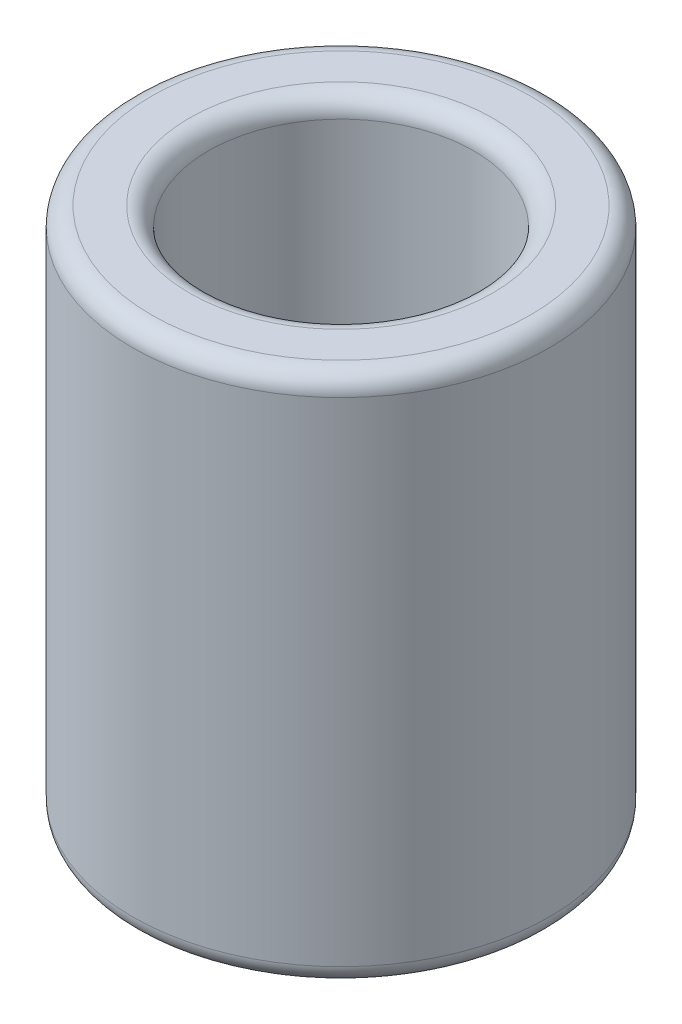
SolidWorks part; units mm, degrees
ref_plane "Front Plane" through (0, 0, 0) normal (0, 0, 1) x (1, 0, 0)
ref_plane "Top Plane" through (0, 0, 0) normal (0, 1, 0) x (1, 0, 0)
ref_plane "Right Plane" through (0, 0, 0) normal (1, 0, 0) x (0, 0, -1)
sketch "Sketch1" plane through (0, 0, 0) normal (0, 1, 0) x (1, 0, 0)
  circle A0 centre (0, 0) radius 1.75
  circle A1 centre (0, 0) radius 2.75
  dimension "D1" = 3.5
  dimension "D2" = 5.5
extrude "Boss-Extrude1" add sketch "Sketch1" along normal blind 7
fillet "Fillet1" radius 0.25 4 edges at (0, 0, 1.75) (0, 0, 2.75) (0, 7, 1.75) (0, 7, 2.75)
